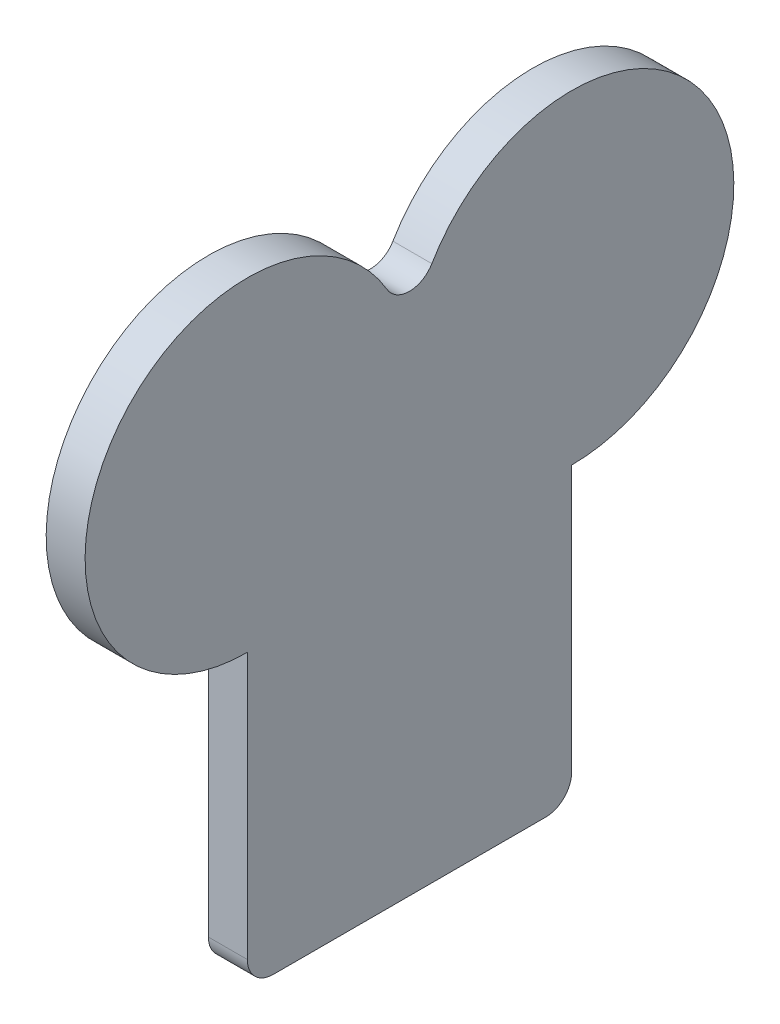
SolidWorks part; units mm, degrees
ref_plane "Front Plane" through (0, 0, 0) normal (0, 0, 1) x (1, 0, 0)
ref_plane "Top Plane" through (0, 0, 0) normal (0, 1, 0) x (1, 0, 0)
ref_plane "Right Plane" through (0, 0, 0) normal (1, 0, 0) x (0, 0, -1)
sketch "Sketch1" plane through (0, 0, 0) normal (1, 0, 0) x (0, 0, -1)
  line L2 (-62.5, 25) -> (-62.5, -87.5)
  line L3 (-62.5, -87.5) -> (62.5, -87.5)
  line L4 (62.5, 25) -> (62.5, -87.5)
  line L5 (-62.5, 87.5) -> (62.5, -87.5) construction
  line L6 (-62.5, -87.5) -> (62.5, 87.5) construction
  arc A0 (0, 87.5) -> (-62.5, 25) centre (-62.5, 87.5) ccw
  arc A1 (62.5, 25) -> (0, 87.5) centre (62.5, 87.5) ccw
  point P0 (0, 0)
  point P9 (0, 87.5)
  point P10 (0, 0)
  point P12 (0, 0)
  dimension "D1" = 125
  dimension "D2" = 175
extrude "Boss-Extrude1" add sketch "Sketch1" along normal blind 15 contours L2 L3 L4 A1 A0
fillet "Fillet1" radius 10 1 edges at (7.5, 87.5, 0)
fillet "Fillet2" radius 10 2 edges at (7.5, -87.5, -62.5) (7.5, -87.5, 62.5)
